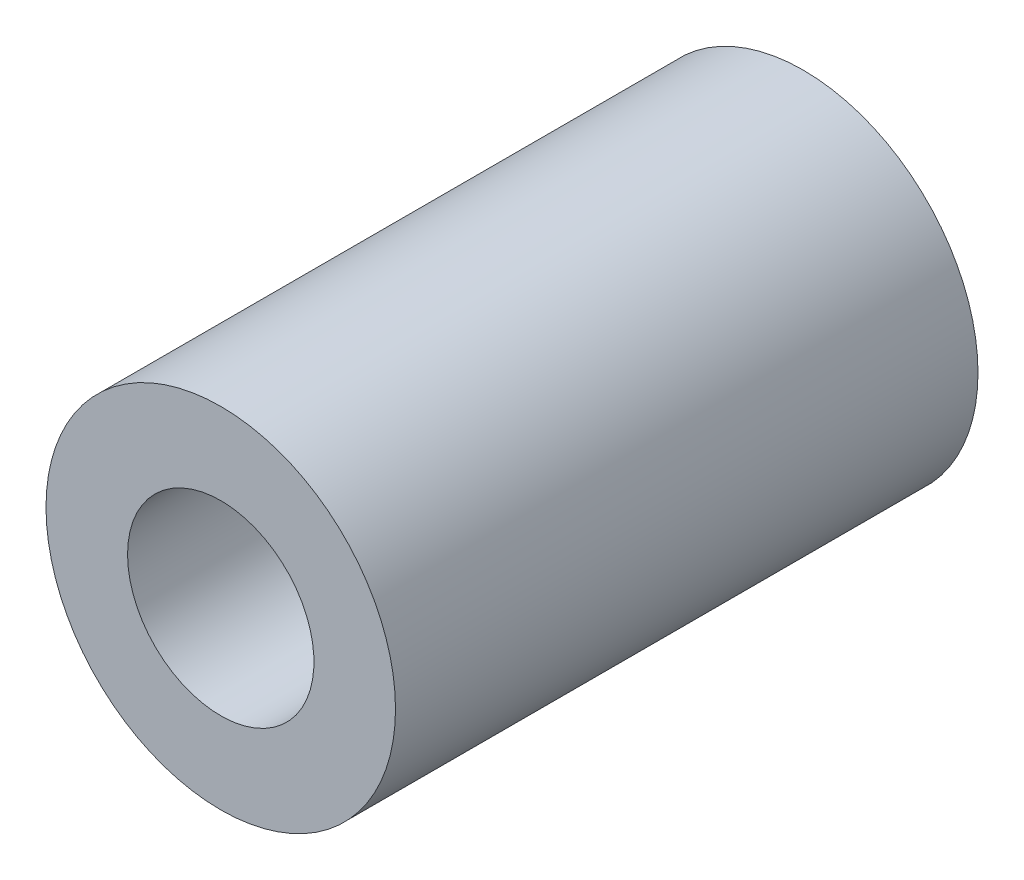
SolidWorks part; units mm, degrees
material "铜"
ref_plane "前视基准面" through (0, 0, 0) normal (0, 0, 1) x (1, 0, 0)
ref_plane "上视基准面" through (0, 0, 0) normal (0, 1, 0) x (1, 0, 0)
ref_plane "右视基准面" through (0, 0, 0) normal (1, 0, 0) x (0, 0, -1)
sketch "草图1" plane through (0, 0, 0) normal (0, 0, 1) x (1, 0, 0)
  circle A0 centre (0, 0) radius 1.5
  dimension "D1" = 3
extrude "凸台-拉伸1" add sketch "草图1" along normal blind 5
hole_wizard "M2 螺纹孔1" positions "草图3" profile "草图4" tap size "M2" standard "GB" end condition through all
sketch "草图3" plane through (0, 0, 0) normal (0, 0, -1) x (-1, 0, 0)
  point P0 (0, 0)
sketch "草图4" plane through (0, 0, 0) normal (1, 0, 0) x (0, 1, 0)
  line L0 (0, 0) -> (0, 5)
  line L1 (0, 5) -> (0.8, 5)
  line L2 (0.8, 5) -> (0.8, 0)
  line L5 (0.8, 0) -> (0, 0)
  line L11 (0, -6.35) -> (0, 107.95) construction
  dimension "通孔螺纹孔钻头直径" = 1.6
  dimension "通孔螺纹孔钻头深度" = 5
cosmetic thread "孔螺蚊线1"
